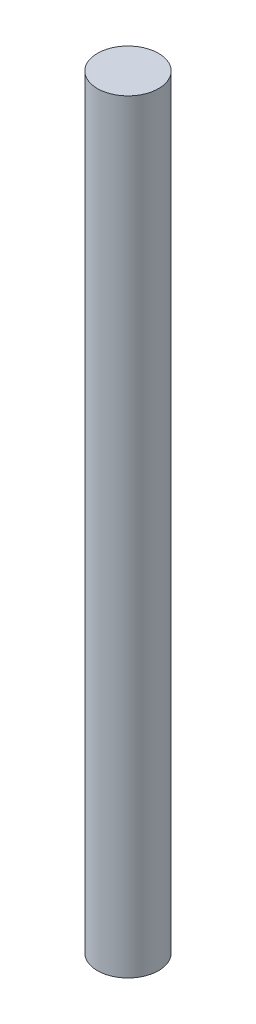
SolidWorks part; units mm, degrees
material "Acero inoxidable al cromo"
ref_plane "Alzado" through (0, 0, 0) normal (0, 0, 1) x (1, 0, 0)
ref_plane "Planta" through (0, 0, 0) normal (0, 1, 0) x (1, 0, 0)
ref_plane "Vista lateral" through (0, 0, 0) normal (1, 0, 0) x (0, 0, -1)
sketch "Croquis1" plane through (0, 0, 0) normal (0, 1, 0) x (1, 0, 0)
  circle A0 centre (0, 0) radius 10
extrude "Saliente-Extruir1" add sketch "Croquis1" along normal blind 250
